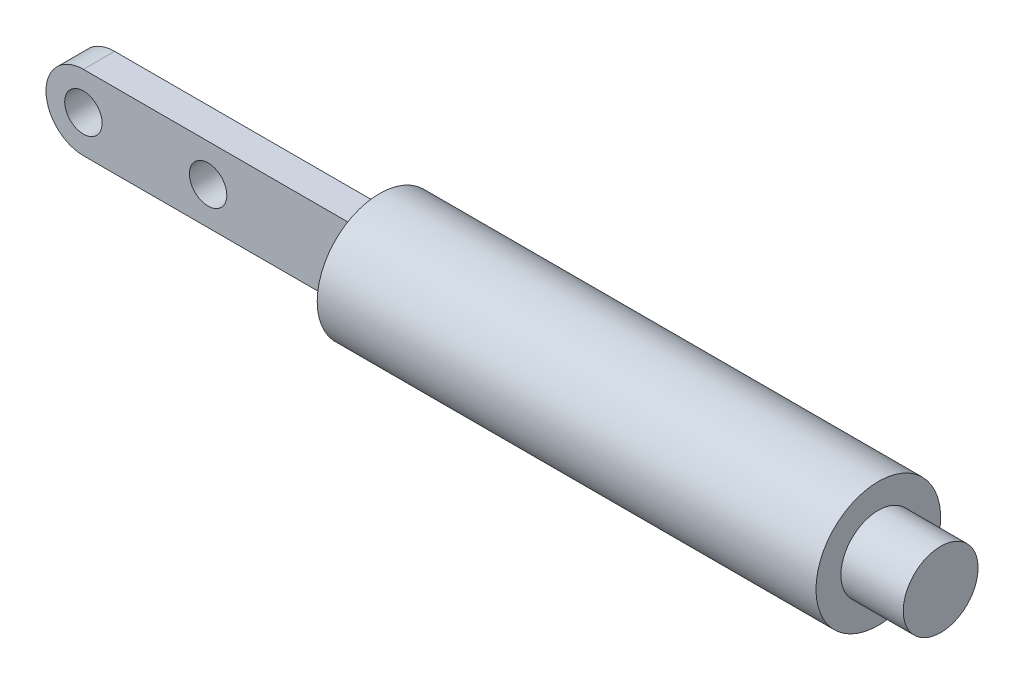
SolidWorks part; units mm, degrees
ref_plane "Front Plane" through (0, 0, 0) normal (0, 0, 1) x (1, 0, 0)
ref_plane "Top Plane" through (0, 0, 0) normal (0, 1, 0) x (1, 0, 0)
ref_plane "Right Plane" through (0, 0, 0) normal (1, 0, 0) x (0, 0, -1)
sketch "Sketch1" plane through (0, 0, 0) normal (0, 1, 0) x (1, 0, 0)
  line L0 (0, 0) -> (90, 0)
  line L1 (90, 0) -> (90, 6)
  line L2 (90, 6) -> (80, 6)
  line L3 (80, 6) -> (80, 10)
  line L4 (80, 10) -> (0, 10)
  line L5 (0, 10) -> (0, 0)
  dimension "D1" = 10
  dimension "D2" = 6
  dimension "D3" = 80
  dimension "D4" = 10
revolve "Revolve1" add sketch "Sketch1" angle 360 about L0
sketch "Sketch2" plane through (0, 0, 0) normal (0, 0, 1) x (1, 0, 0)
  line L0 (-12.8584, 0) -> (123.6309, 0) construction
  line L1 (0, 10) -> (0, -10) construction
  line L2 (0, 10) -> (0, -10)
  line L5 (0, 6) -> (-45, 6)
  line L6 (-45, -6) -> (0, -6)
  line L7 (-12.8584, 0) -> (-51, 0) construction
  line L8 (0, 6) -> (0, -6)
  arc A1 (-45, 6) -> (-45, -6) centre (-45, 0) ccw
  circle A2 centre (-45, 0) radius 3
  circle A3 centre (-25, 0) radius 3
  dimension "D1" = 12
  dimension "D2" = 6
  dimension "D4" = 6
  dimension "D3" = 45
  dimension "D5" = 25
extrude "Boss-Extrude1" add sketch "Sketch2" along normal mid plane 5 contours L5 A1 L6 L2 A3 A2
